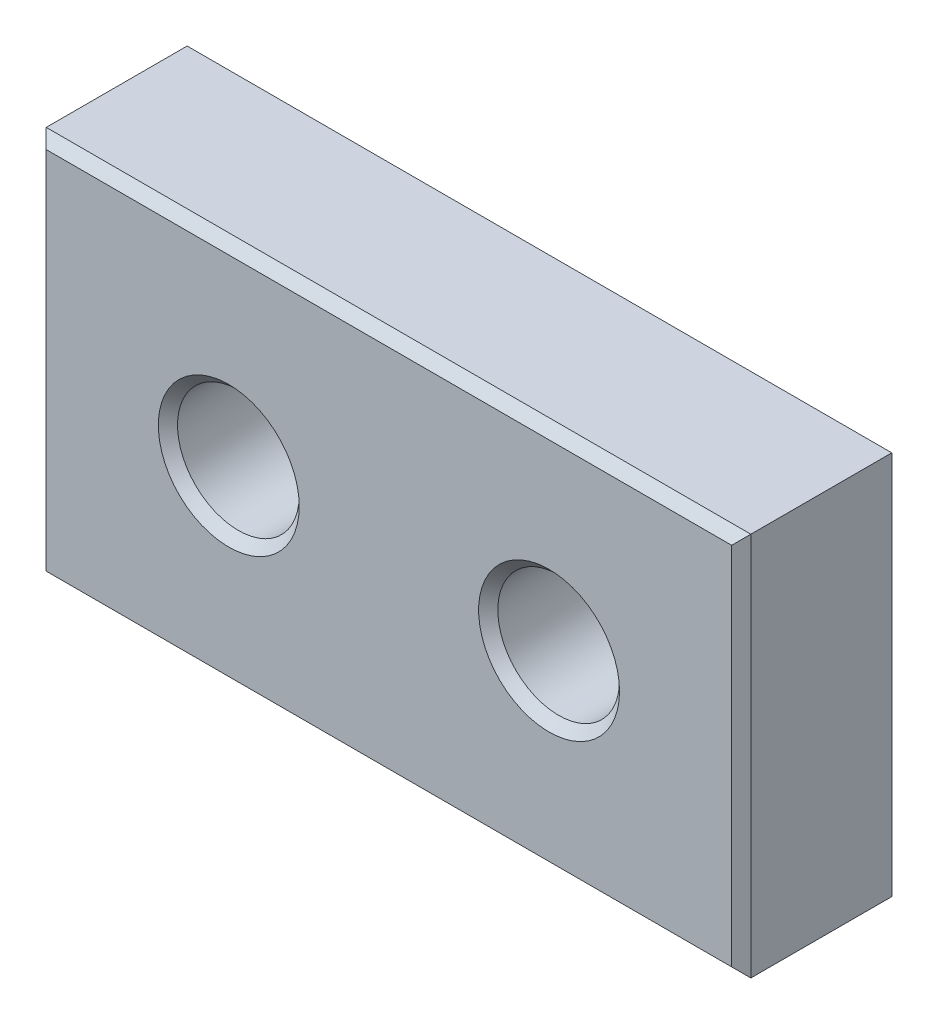
SolidWorks part; units mm, degrees
ref_plane "정면" through (0, 0, 0) normal (0, 0, 1) x (1, 0, 0)
ref_plane "윗면" through (0, 0, 0) normal (0, 1, 0) x (1, 0, 0)
ref_plane "우측면" through (0, 0, 0) normal (1, 0, 0) x (0, 0, -1)
sketch "스케치1" plane through (0, 0, 0) normal (0, 0, 1) x (1, 0, 0)
  line L0 (0, 0) -> (-5, 0) construction
  line L1 (-11, 6) -> (11, 6)
  line L2 (-11, 6) -> (-11, -6)
  line L3 (-11, -6) -> (11, -6)
  line L4 (11, 6) -> (11, -6)
  line L5 (-11, 6) -> (11, -6) construction
  line L6 (-11, -6) -> (11, 6) construction
  line L7 (0, 0) -> (0, 6) construction
  circle A0 centre (-5, 0) radius 1.9
  circle A1 centre (5, 0) radius 1.9
  point P0 (0, 0)
  dimension "D3" = 3.8
  dimension "D1" = 12
  dimension "D2" = 22
  dimension "D4" = 10
extrude "보스-돌출1" add sketch "스케치1" along normal blind 5
chamfer "모따기1" distance 0.3 angle 45 12 edges at (3.1, 0, 0) (-3.1, 0, 0) (0, 6, 0) (-11, 0, 0) (0, -6, 0) (11, 0, 0) (3.1, 0, 5) (0, -6, 5) (-11, 0, 5) (0, 6, 5) (11, 0, 5) (-3.1, 0, 5)
